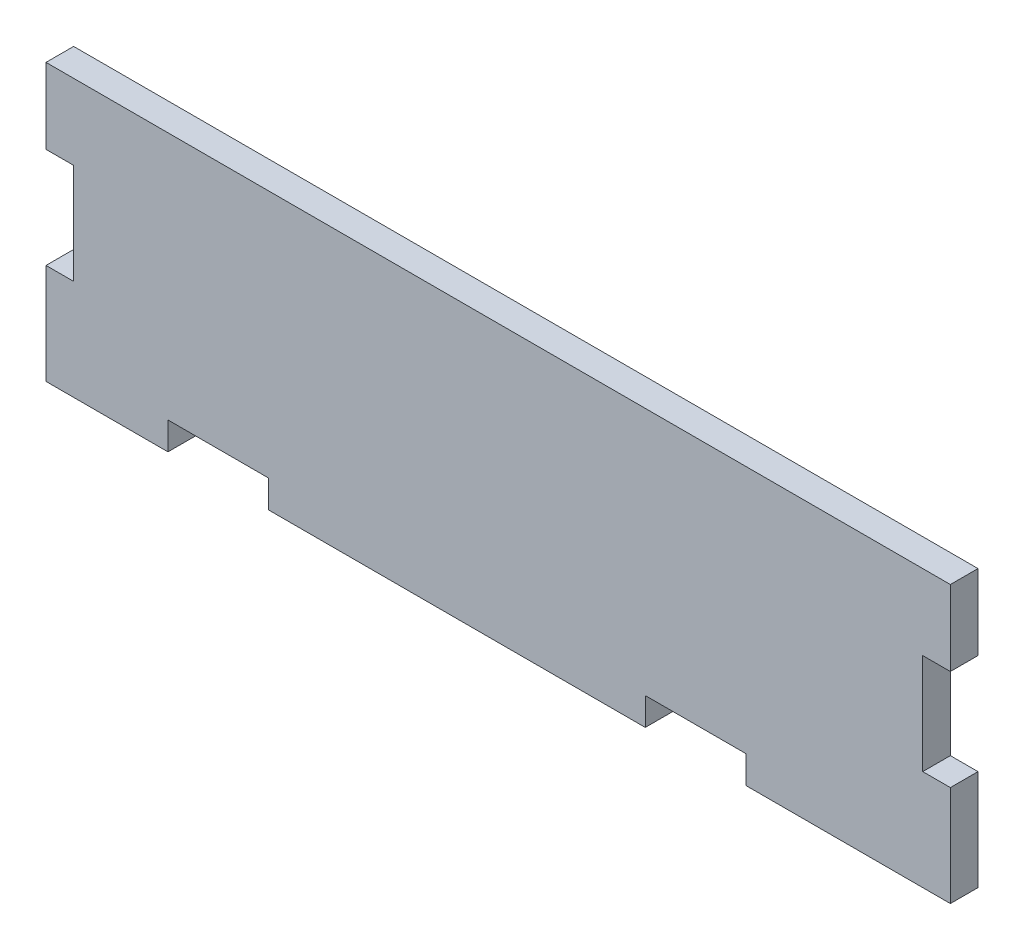
SolidWorks part; units mm, degrees
ref_plane "Front Plane" through (0, 0, 0) normal (0, 0, 1) x (1, 0, 0)
ref_plane "Top Plane" through (0, 0, 0) normal (0, 1, 0) x (1, 0, 0)
ref_plane "Right Plane" through (0, 0, 0) normal (1, 0, 0) x (0, 0, -1)
sketch "Sketch1" plane through (0, 0, 0) normal (0, 0, 1) x (1, 0, 0)
  line L1 (8.2245, 0) -> (32.5, 0)
  line L3 (8.2245, 55) -> (188.2245, 55)
  line L4 (188.2245, 0) -> (188.2245, 20)
  line L5 (182.7245, 40) -> (182.7245, 20)
  line L10 (0, 30) -> (94.1123, 30) construction
  line L13 (100, 0) -> (127.5, 0)
  line L15 (8.2245, 0) -> (188.2245, 0) construction
  line L16 (182.7245, 20) -> (188.2245, 20)
  line L17 (13.7245, 5.5) -> (182.7245, 5.5) construction
  line L18 (182.7245, 40) -> (188.2245, 40)
  line L19 (13.7245, 5.5) -> (13.7245, 49.5) construction
  line L20 (13.7245, 49.5) -> (182.7245, 49.5) construction
  line L21 (182.7245, 5.5) -> (182.7245, 49.5) construction
  line L22 (188.2245, 40) -> (188.2245, 55)
  line L23 (188.2245, 0) -> (188.2245, 55) construction
  line L25 (8.2245, 0) -> (8.2245, 55) construction
  line L26 (80, 0) -> (100, 0)
  line L27 (32.5, 5.5) -> (52.5, 5.5)
  line L28 (32.5, 5.5) -> (32.5, 0)
  line L30 (52.5, 5.5) -> (52.5, 0)
  line L31 (127.5, 5.5) -> (147.5, 5.5)
  line L32 (127.5, 5.5) -> (127.5, 0)
  line L34 (147.5, 5.5) -> (147.5, 0)
  line L35 (147.5, 0) -> (188.2245, 0)
  line L36 (52.5, 0) -> (80, 0)
  line L37 (182.7245, 20) -> (182.7245, 40) construction
  line L41 (8.2245, 40.25) -> (8.2245, 55) construction
  line L42 (8.2245, 55) -> (8.2245, 40)
  line L43 (8.2245, 40) -> (13.7245, 40)
  line L44 (13.7245, 40) -> (13.7245, 20)
  line L45 (13.7245, 20) -> (8.2245, 20)
  line L46 (8.2245, 20) -> (8.2245, 0)
  dimension "D2" = 55
  dimension "D4" = 5.5
  dimension "D5" = 20
  dimension "D8" = 10
  dimension "D9" = 5.5
  dimension "D3" = 5.5
extrude "Boss-Extrude1" add sketch "Sketch1" along normal blind 5.5
